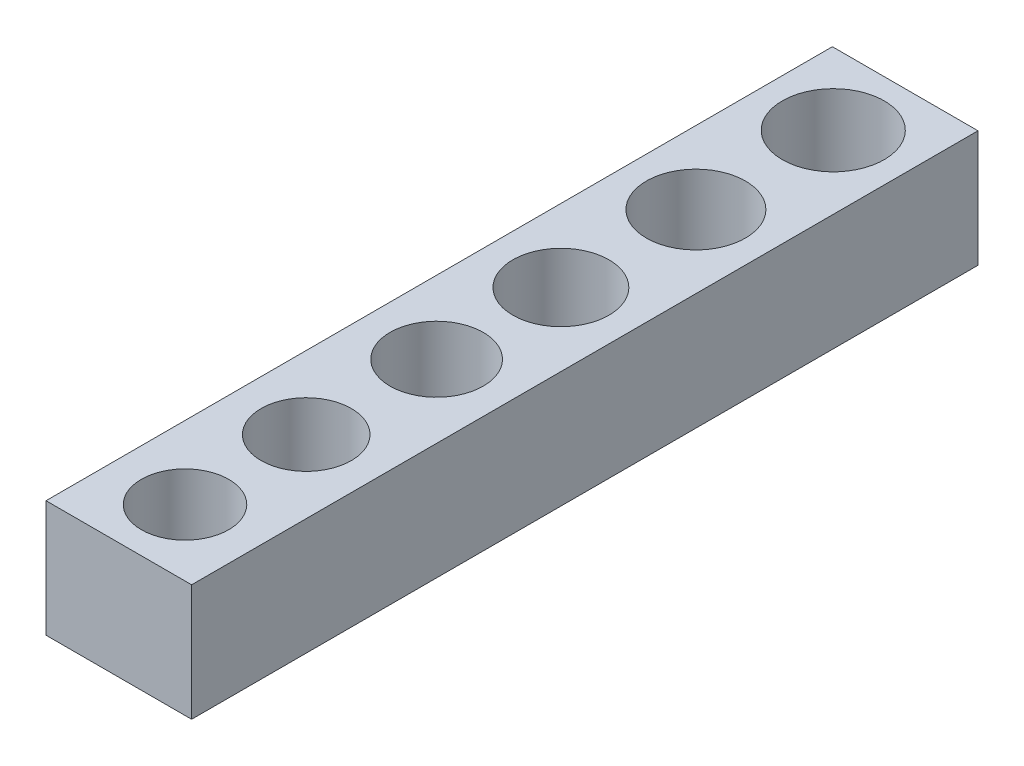
SolidWorks part; units mm, degrees
ref_plane "Alzado" through (0, 0, 0) normal (0, 0, 1) x (1, 0, 0)
ref_plane "Planta" through (0, 0, 0) normal (0, 1, 0) x (1, 0, 0)
ref_plane "Vista lateral" through (0, 0, 0) normal (1, 0, 0) x (0, 0, -1)
sketch "Croquis3" plane through (0, 0, 0) normal (0, 1, 0) x (1, 0, 0)
  line L0 (0, 39.8494) -> (0, -30.9156) construction
  line L1 (5, -29) -> (-5, -29)
  line L2 (5, -29) -> (5, 25)
  line L3 (5, 25) -> (-5, 25)
  line L4 (-5, -29) -> (-5, 25)
  line L5 (5, -29) -> (-5, 25) construction
  line L6 (5, 25) -> (-5, -29) construction
  circle A2 centre (0, -16.1307) radius 3.1
  circle A3 centre (0, 1.3588) radius 3.3
  circle A4 centre (0, 10.6304) radius 3.4
  circle A5 centre (0, 20.0613) radius 3.5
  circle A6 centre (0, -24.4541) radius 3
  circle A7 centre (0, -7.1752) radius 3.2
  point P0 (0, -2.9063)
  point P6 (0, -3.6003)
  point P7 (0, 5.0115)
  point P14 (0, -20.032)
  point P15 (0, -12.1048)
  point P16 (0, 0)
  point P23 (0, 0)
  point P24 (0, 0)
  point P25 (0, -2.9063)
  point P26 (0, 0)
  point P27 (0, 20.0613)
  point P28 (0, 11.4495)
  point P29 (0, 3.0885)
  point P32 (0, -4.8544)
  point P33 (0, -12.881)
  point P34 (0, -24.4541)
  point P35 (0, -16.1307)
  point P36 (0, -7.1752)
  point P37 (0, 1.3588)
  point P38 (0, 10.6304)
  dimension "D3" = 6.4
  dimension "D4" = 6.2
  dimension "D5" = 6.6
  dimension "D6" = 6.8
  dimension "D7" = 7
  dimension "D8" = 6
  dimension "D1" = 10
  dimension "D2" = 54
extrude "Saliente-Extruir1" add sketch "Croquis3" along normal blind 8
